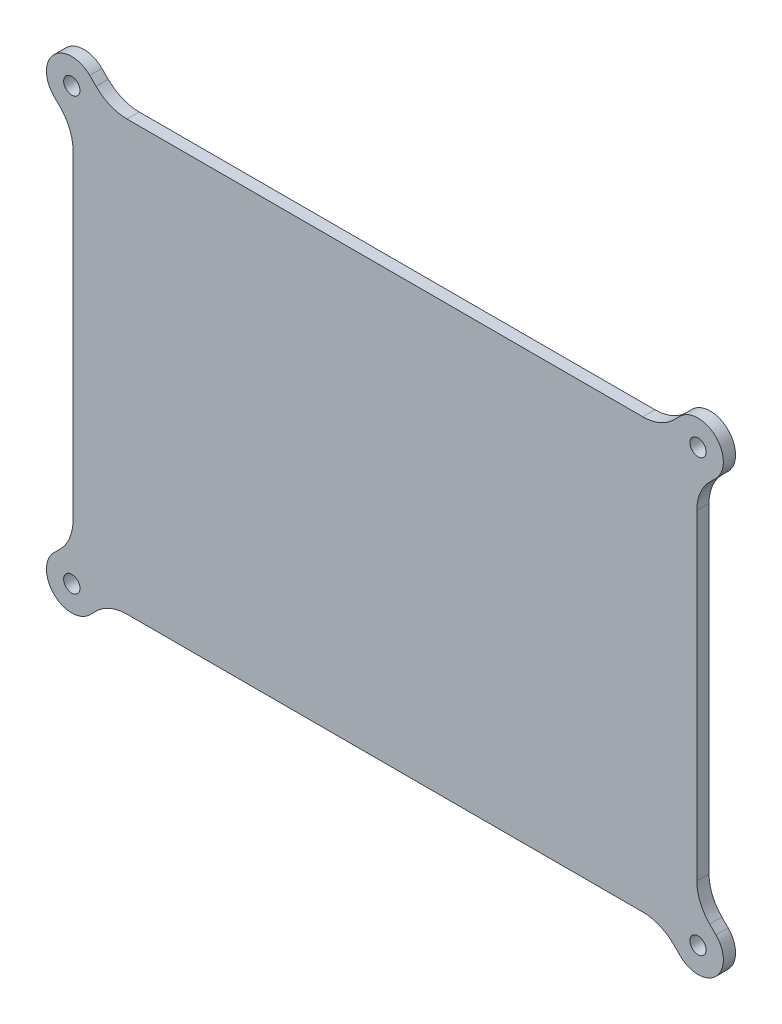
SolidWorks part; units mm, degrees
ref_plane "Front Plane" through (0, 0, 0) normal (0, 0, 1) x (1, 0, 0)
ref_plane "Top Plane" through (0, 0, 0) normal (0, 1, 0) x (1, 0, 0)
ref_plane "Right Plane" through (0, 0, 0) normal (1, 0, 0) x (0, 0, -1)
sketch "Sketch1" plane through (0, 0, 0) normal (0, 0, 1) x (1, 0, 0)
  line L0 (-86.5604, 44.1022) -> (-86.5604, -39.4879) construction
  line L7 (-91.5438, -49.2058) -> (-89.9082, -47.5702) construction
  line L8 (-82.1933, -58.5562) -> (-80.5577, -56.9206) construction
  line L9 (61.9147, -53.5728) -> (-72.4755, -53.5728) construction
  line L10 (71.6325, -58.5562) -> (69.9969, -56.9206) construction
  line L11 (80.983, -49.2058) -> (79.3474, -47.5702) construction
  line L12 (75.9996, 44.1022) -> (75.9996, -39.4879) construction
  line L13 (80.983, 53.8201) -> (79.3474, 52.1845) construction
  line L14 (71.6325, 63.1705) -> (69.9969, 61.5349) construction
  line L15 (61.9147, 58.1872) -> (-72.4755, 58.1872) construction
  line L16 (-91.5438, 53.8201) -> (-89.9082, 52.1845) construction
  line L17 (-82.1933, 63.1705) -> (-80.5577, 61.5349) construction
  line L18 (-86.5604, 44.1022) -> (-86.5604, -39.4879)
  line L19 (-91.5438, -49.2058) -> (-89.9082, -47.5702)
  line L20 (-82.1933, -58.5562) -> (-80.5577, -56.9206)
  line L21 (61.9147, -53.5728) -> (-72.4755, -53.5728)
  line L22 (71.6325, -58.5562) -> (69.9969, -56.9206)
  line L23 (80.983, -49.2058) -> (79.3474, -47.5702)
  line L24 (75.9996, 44.1022) -> (75.9996, -39.4879)
  line L25 (80.983, 53.8201) -> (79.3474, 52.1845)
  line L26 (71.6325, 63.1705) -> (69.9969, 61.5349)
  line L27 (61.9147, 58.1872) -> (-72.4755, 58.1872)
  line L28 (-91.5438, 53.8201) -> (-89.9082, 52.1845)
  line L29 (-82.1933, 63.1705) -> (-80.5577, 61.5349)
  arc A0 (-89.9082, -47.5702) -> (-86.5604, -39.4879) centre (-97.9904, -39.4879) ccw construction
  arc A1 (-91.5438, -49.2058) -> (-82.1933, -58.5562) centre (-86.8686, -53.881) ccw construction
  arc A2 (-72.4755, -53.5728) -> (-80.5577, -56.9206) centre (-72.4755, -65.0028) ccw construction
  arc A3 (69.9969, -56.9206) -> (61.9147, -53.5728) centre (61.9147, -65.0028) ccw construction
  arc A4 (71.6325, -58.5562) -> (80.983, -49.2058) centre (76.3077, -53.881) ccw construction
  arc A5 (75.9996, -39.4879) -> (79.3474, -47.5702) centre (87.4296, -39.4879) ccw construction
  arc A6 (79.3474, 52.1845) -> (75.9996, 44.1022) centre (87.4296, 44.1022) ccw construction
  arc A7 (80.983, 53.8201) -> (71.6325, 63.1705) centre (76.3077, 58.4953) ccw construction
  arc A8 (61.9147, 58.1872) -> (69.9969, 61.5349) centre (61.9147, 69.6172) ccw construction
  arc A9 (-86.5604, 44.1022) -> (-89.9082, 52.1845) centre (-97.9904, 44.1022) ccw construction
  arc A10 (-82.1933, 63.1705) -> (-91.5438, 53.8201) centre (-86.8686, 58.4953) ccw construction
  arc A11 (-80.5577, 61.5349) -> (-72.4755, 58.1872) centre (-72.4755, 69.6172) ccw construction
  arc A12 (-89.9082, -47.5702) -> (-86.5604, -39.4879) centre (-97.9904, -39.4879) ccw
  arc A13 (-91.5438, -49.2058) -> (-82.1933, -58.5562) centre (-86.8686, -53.881) ccw
  arc A14 (-72.4755, -53.5728) -> (-80.5577, -56.9206) centre (-72.4755, -65.0028) ccw
  arc A15 (69.9969, -56.9206) -> (61.9147, -53.5728) centre (61.9147, -65.0028) ccw
  arc A16 (71.6325, -58.5562) -> (80.983, -49.2058) centre (76.3077, -53.881) ccw
  arc A17 (75.9996, -39.4879) -> (79.3474, -47.5702) centre (87.4296, -39.4879) ccw
  arc A18 (79.3474, 52.1845) -> (75.9996, 44.1022) centre (87.4296, 44.1022) ccw
  arc A19 (80.983, 53.8201) -> (71.6325, 63.1705) centre (76.3077, 58.4953) ccw
  arc A20 (61.9147, 58.1872) -> (69.9969, 61.5349) centre (61.9147, 69.6172) ccw
  arc A21 (-86.5604, 44.1022) -> (-89.9082, 52.1845) centre (-97.9904, 44.1022) ccw
  arc A22 (-82.1933, 63.1705) -> (-91.5438, 53.8201) centre (-86.8686, 58.4953) ccw
  arc A23 (-80.5577, 61.5349) -> (-72.4755, 58.1872) centre (-72.4755, 69.6172) ccw
  circle A24 centre (-86.8686, 58.4953) radius 2.125
  circle A25 centre (76.3077, 58.4953) radius 2.125
  circle A26 centre (76.3077, -53.881) radius 2.125
  circle A27 centre (-86.8686, -53.881) radius 2.125
  point P0 (0, 0)
  dimension "D1" = 4.25
extrude "Boss-Extrude1" add sketch "Sketch1" along normal blind 3.175
